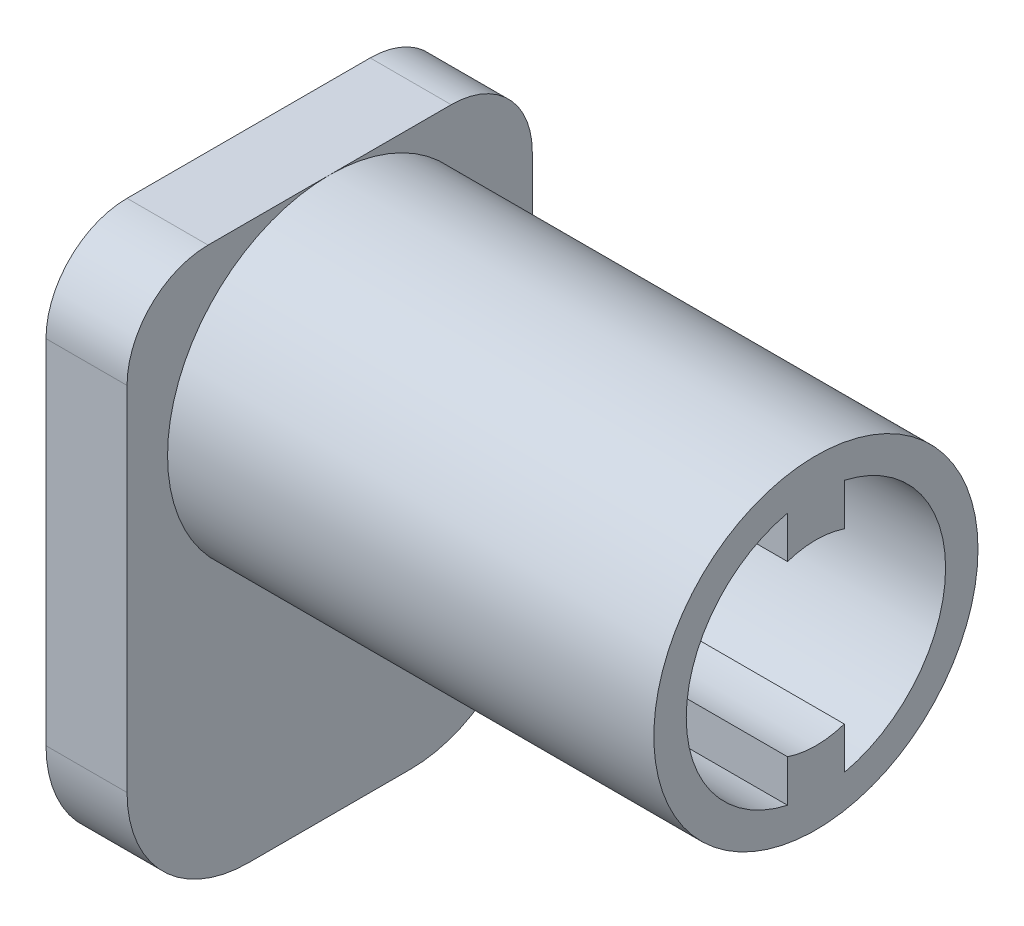
SolidWorks part; units mm, degrees
ref_plane "Front Plane" through (0, 0, 0) normal (0, 0, 1) x (1, 0, 0)
ref_plane "Top Plane" through (0, 0, 0) normal (0, 1, 0) x (1, 0, 0)
ref_plane "Right Plane" through (0, 0, 0) normal (1, 0, 0) x (0, 0, -1)
sketch "Sketch2" plane through (0, 0, 0) normal (1, 0, 0) x (0, 0, -1)
  circle A0 centre (0, 0) radius 4
  dimension "D1" = 8
extrude "Boss-Extrude1" add sketch "Sketch2" against normal blind 12
sketch "Sketch3" plane through (-12, 0, 0) normal (-1, 0, 0) x (0, 0, 1)
  line L0 (0, 0) -> (0, -9.7) construction
  line L1 (-5, 4) -> (5, 4)
  line L2 (-5, 4) -> (-5, -9.7)
  line L3 (-5, -9.7) -> (5, -9.7)
  line L4 (5, 4) -> (5, -9.7)
  dimension "D1" = 9.7
  dimension "D2" = 4
  dimension "D3" = 10
extrude "Boss-Extrude2" add sketch "Sketch3" along normal blind 2
sketch "Sketch4" plane through (0, 0, 0) normal (1, 0, 0) x (0, 0, -1)
  circle A0 centre (0, 0) radius 3.2
  dimension "D1" = 6.4
extrude "Cut-Extrude1" cut sketch "Sketch4" against normal up to surface (12 mm away) up to face at (-12, -1.2333, -0.6667)
sketch "Sketch6" plane through (-14, 0, 0) normal (-1, 0, 0) x (0, 0, 1)
  line L6 (0.7, -2.8618) -> (0.7, -1.7861)
  line L7 (0.7, -2.8618) -> (0.7, -2.0857)
  line L8 (-0.7, -2.8618) -> (0.7, -2.8618) construction
  line L9 (-0.7, -1.7861) -> (-0.7, -2.8618)
  line L10 (-0.7, -2.0857) -> (-0.7, -2.8618)
  line L12 (0, 0) -> (5, 0) construction
  line L13 (5, -9.7) -> (5, 4) construction
  line L15 (-0.7, 2.0857) -> (-0.7, 2.8618)
  line L16 (-0.7, 2.8618) -> (0.7, 2.8618) construction
  line L17 (0.7, 2.8618) -> (0.7, 2.0857)
  line L18 (-0.7, -2.8618) -> (-0.7, -3.1225)
  line L19 (0.7, -2.8618) -> (0.7, -3.1225)
  line L20 (-0.7, 2.8618) -> (-0.7, 3.1225)
  line L21 (0.7, 2.8618) -> (0.7, 3.1225)
  arc A1 (-0.7, 2.0857) -> (0.7, 2.0857) centre (0, 0) cw
  arc A2 (-0.99, -1.9647) -> (0.99, -1.9647) centre (0, 0) ccw
  arc A3 (-0.7, -2.0857) -> (0.7, -2.0857) centre (0, 0) ccw
  circle A4 centre (0, 0) radius 3.2 construction
  arc A5 (-0.7, -3.1225) -> (0.7, -3.1225) centre (0, 0) ccw
  arc A6 (-0.7, 3.1225) -> (0.7, 3.1225) centre (0, 0) cw
  dimension "D3" = 0.2
  dimension "D1" = 0.2
  dimension "D2" = 0.2
sketch "Sketch7" plane through (-14, 0, 0) normal (-1, 0, 0) x (0, 0, 1)
  circle A0 centre (0, 0) radius 1.6
  dimension "D1" = 3.2
extrude "Cut-Extrude4" cut sketch "Sketch7" against normal through all
extrude "Boss-Extrude3" add sketch "Sketch6" against normal up to surface (14 mm away) up to face at (0, 0, -3.2)
fillet "Fillet2" radius 2 2 edges at (-13, 4, 5) (-13, 4, -5)
fillet "Fillet3" radius 3 2 edges at (-13, -9.7, -5) (-13, -9.7, 5)
